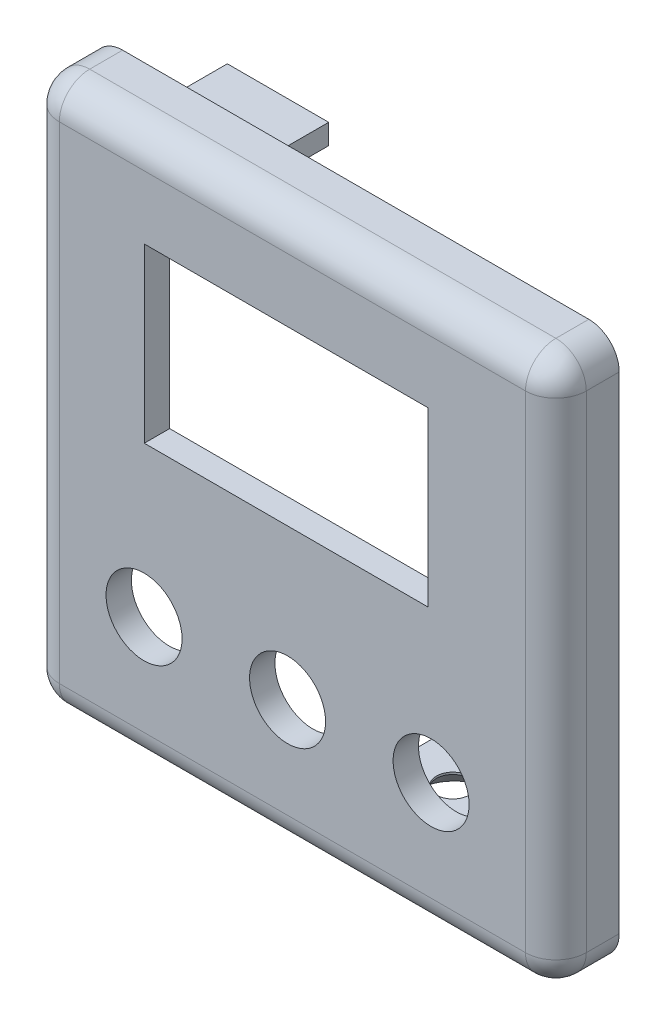
SolidWorks part; units mm, degrees
ref_plane "Alzado" through (0, 0, 0) normal (0, 0, 1) x (1, 0, 0)
ref_plane "Planta" through (0, 0, 0) normal (0, 1, 0) x (1, 0, 0)
ref_plane "Vista lateral" through (0, 0, 0) normal (1, 0, 0) x (0, 0, -1)
sketch "Croquis1" plane through (0, 0, 0) normal (0, 0, 1) x (1, 0, 0)
  line L5 (-25.1623, 26.4339) -> (20.8377, 26.4339)
  line L6 (-28.1623, 23.4339) -> (-28.1623, -24.5661)
  line L7 (-25.1623, -27.5661) -> (20.8377, -27.5661)
  line L8 (23.8377, 23.4339) -> (23.8377, -24.5661)
  line L9 (-25.1623, 22.4339) -> (20.8377, 22.4339)
  line L10 (-25.1623, 22.4339) -> (-25.1623, -23.5661)
  line L11 (-25.1623, -23.5661) -> (20.8377, -23.5661)
  line L12 (20.8377, 22.4339) -> (20.8377, -23.5661)
  arc A0 (-28.1623, 23.4339) -> (-25.1623, 26.4339) centre (-25.1623, 23.4339) cw
  arc A1 (-25.1623, -27.5661) -> (-28.1623, -24.5661) centre (-25.1623, -24.5661) cw
  arc A2 (20.8377, -27.5661) -> (23.8377, -24.5661) centre (20.8377, -24.5661) ccw
  arc A3 (20.8377, 26.4339) -> (23.8377, 23.4339) centre (20.8377, 23.4339) cw
  dimension "D1" = 3
  dimension "D2" = 23.8377
  dimension "D3" = 28.1623
  dimension "D4" = 22.4339
  dimension "D5" = 26.4339
  dimension "D6" = 27.5661
extrude "Saliente-Extruir1" add sketch "Croquis1" along normal blind 3.75
sketch "Croquis2" plane through (0, 0, 0) normal (0, 0, -1) x (-1, 0, 0)
  line L0 (25.1623, -27.5661) -> (-20.8377, -27.5661) construction
  line L1 (-6.9727, -25.5661) -> (3.0273, -25.5661)
  line L2 (-6.9727, -25.5661) -> (-6.9727, -27.5661)
  line L3 (-6.9727, -27.5661) -> (3.0273, -27.5661)
  line L4 (3.0273, -25.5661) -> (3.0273, -27.5661)
  line L12 (28.1623, 23.4339) -> (28.1623, -24.5661) construction
  line L13 (-20.8377, 26.4339) -> (25.1623, 26.4339) construction
  dimension "D1" = 25.135
  dimension "D2" = 35.135
  dimension "D3" = 52
extrude "Saliente-Extruir2" add sketch "Croquis2" along normal blind 8.7
sketch "Croquis5" plane through (0, 0, 0) normal (0, 0, -1) x (-1, 0, 0)
  line L1 (10.8309, 24.4339) -> (20.8309, 24.4339)
  line L2 (10.8309, 24.4339) -> (10.8309, 22.4339)
  line L3 (10.8309, 22.4339) -> (20.8309, 22.4339)
  line L4 (20.8309, 24.4339) -> (20.8309, 22.4339)
  line L6 (-20.8377, -23.5661) -> (-20.8377, 22.4339) construction
  line L7 (-20.8377, 22.4339) -> (25.1623, 22.4339) construction
  dimension "D1" = 31.6686
  dimension "D2" = 41.6686
  dimension "D3" = 2
extrude "Saliente-Extruir3" add sketch "Croquis5" along normal blind 6
sketch "Croquis6" plane through (0, -25.5661, 0) normal (0, 1, 0) x (1, 0, 0)
  line L0 (6.9727, 8.7) -> (6.9727, 0) construction
  line L1 (-3.0273, 0) -> (6.9727, 0) construction
  circle A0 centre (1.9727, 5.45) radius 1.625
  dimension "D1" = 3.25
  dimension "D2" = 5
  dimension "D3" = 5.45
extrude "Cortar-Extruir1" cut sketch "Croquis6" against normal up to vertex (2 mm away)
sketch "Croquis7" plane through (0, -27.5661, 0) normal (0, -1, 0) x (1, 0, 0)
  line L0 (6.9727, -8.7) -> (6.9727, 0) construction
  line L1 (6.9727, -8.7) -> (-3.0273, -8.7) construction
  circle A0 centre (1.9727, -5.45) radius 3.36
  dimension "D1" = 6.7199
  dimension "D2" = 5
  dimension "D3" = 3.25
extrude "Cortar-Extruir2" cut sketch "Croquis7" against normal blind 1.8 draft 44
sketch "Croquis9" plane through (-3.0273, 0, 0) normal (-1, 0, 0) x (0, 0, 1)
  line L0 (-8.7, -27.3752) -> (-8.7, -27.5661)
  line L1 (-8.7, -27.5661) -> (-8.7, -25.5661) construction
  line L2 (-8.7, -27.5661) -> (0, -27.5661) construction
  line L6 (-7.7, -27.5661) -> (-8.7, -27.5661)
  line L7 (0, -27.5661) -> (0, -25.5661) construction
  arc A1 (-8.7, -27.3752) -> (-7.7, -27.5661) centre (-7.1112, -21.7673) ccw
  dimension "D1" = 5.8286
  dimension "D2" = 7.1112
  dimension "D3" = 7.7
extrude "Cortar-Extruir3" cut sketch "Croquis9" against normal up to vertex (10 mm away)
sketch "Croquis10" plane through (0, 0, 3.75) normal (0, 0, 1) x (1, 0, 0)
  line L0 (20.8377, 26.4339) -> (-25.1623, 26.4339) construction
  line L1 (-16.7736, 17.1902) -> (11.2264, 17.1902)
  line L2 (-16.7736, 17.1902) -> (-16.7736, 0.1639)
  line L3 (-16.7736, 0.1639) -> (11.2264, 0.1639)
  line L4 (23.8377, -24.5661) -> (23.8377, 23.4339) construction
  line L5 (-25.1623, 26.4339) -> (20.8377, 26.4339)
  line L6 (11.2264, 17.1902) -> (11.2264, 0.1639)
  line L7 (-28.1623, 23.4339) -> (-28.1623, -24.5661)
  line L8 (-25.1623, -27.5661) -> (20.8377, -27.5661)
  line L9 (23.8377, 23.4339) -> (23.8377, -24.5661)
  arc A0 (-25.1623, 26.4339) -> (-28.1623, 23.4339) centre (-25.1623, 23.4339) ccw construction
  arc A1 (20.8377, -27.5661) -> (23.8377, -24.5661) centre (20.8377, -24.5661) ccw construction
  arc A2 (-28.1623, 23.4339) -> (-25.1623, 26.4339) centre (-25.1623, 23.4339) cw
  arc A3 (23.8377, -24.5661) -> (20.8377, -27.5661) centre (20.8377, -24.5661) cw
  arc A4 (20.8377, 26.4339) -> (23.8377, 23.4339) centre (20.8377, 23.4339) cw
  arc A5 (23.8377, 23.4339) -> (20.8377, 26.4339) centre (20.8377, 23.4339) ccw construction
  arc A6 (-25.1623, -27.5661) -> (-28.1623, -24.5661) centre (-25.1623, -24.5661) cw
  circle A7 centre (-16.7998, -14.6911) radius 3.75
  circle A8 centre (-2.6373, -14.6911) radius 3.75
  circle A9 centre (11.5252, -14.6911) radius 3.75
  dimension "D1" = 7.5
  dimension "D2" = 12.3125
  dimension "D3" = 12.6113
  dimension "D4" = 26.475
  dimension "D5" = 40.6113
  dimension "D6" = 40.6375
  dimension "D7" = 9.2438
  dimension "D8" = 26.27
  dimension "D9" = 41.125
extrude "Saliente-Extruir4" add sketch "Croquis10" along normal blind 2.5
fillet "Redondeo1" radius 3 8 edges at (-27.2836, 25.5553, 6.25) (-2.1623, 26.4339, 6.25) (22.959, 25.5553, 6.25) (23.8377, -0.5661, 6.25) (22.959, -26.6874, 6.25) (-2.1623, -27.5661, 6.25) (-27.2836, -26.6874, 6.25) (-28.1623, -0.5661, 6.25)
